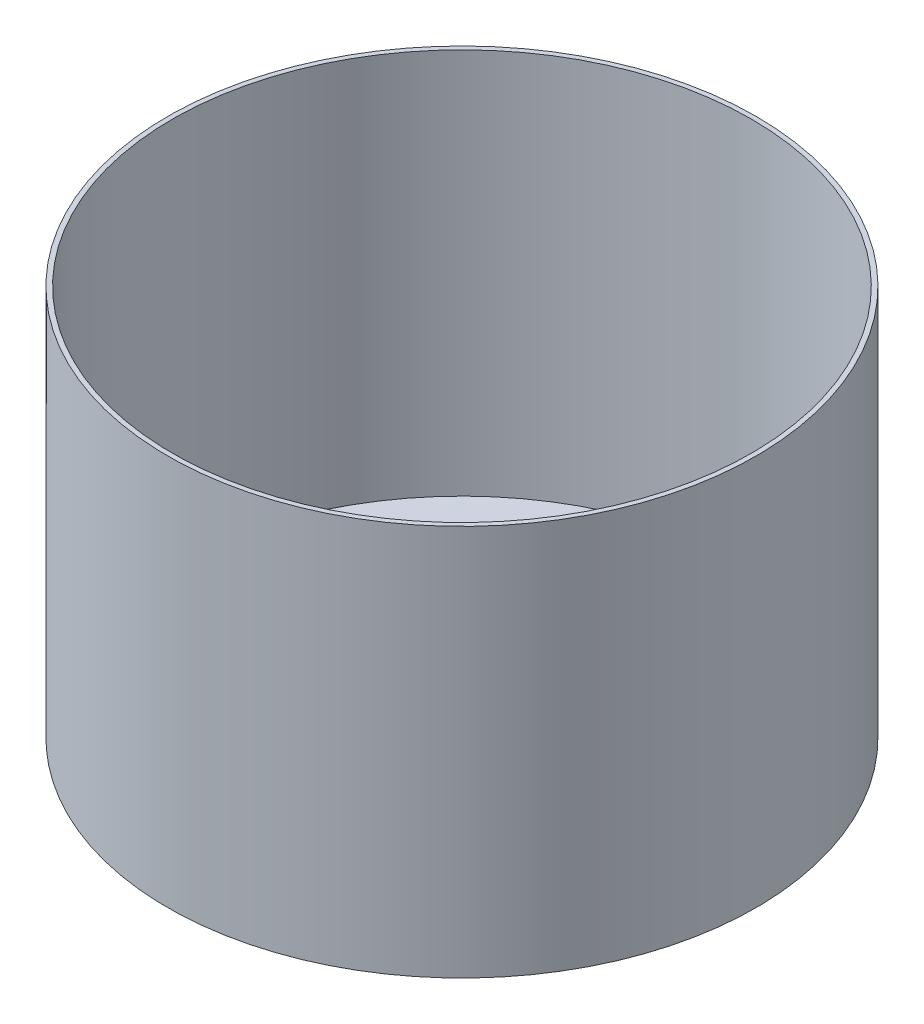
SolidWorks part; units mm, degrees
ref_plane "Front Plane" through (0, 0, 0) normal (0, 0, 1) x (1, 0, 0)
ref_plane "Top Plane" through (0, 0, 0) normal (0, 1, 0) x (1, 0, 0)
ref_plane "Right Plane" through (0, 0, 0) normal (1, 0, 0) x (0, 0, -1)
sketch "Compartment" plane through (0, 0, 0) normal (0, 0, 1) x (1, 0, 0)
  line L3 (95.504, -80) -> (0, -80)
  line L6 (93.98, 47) -> (95.504, 47)
  line L9 (93.98, 47) -> (93.98, -78.476)
  line L10 (93.98, -78.476) -> (0, -78.476)
  line L11 (0, -78.476) -> (0, -80)
  line L14 (95.504, 47) -> (95.504, -80)
  dimension "D1" = 125.476
  dimension "D2" = 1.524
  dimension "D5" = 93.98
  dimension "D6" = 1.524
  dimension "D9" = 80
ref_axis "Axis1" through (0, 0, 0) along (0, 1, 0)
revolve "Revolve1" add sketch "Compartment" angle 360 about axis through (0, 0, 0) along (0, 1, 0)
sketch "Motor Hole" plane through (0, -80, 0) normal (0, -1, 0) x (1, 0, 0)
  circle A0 centre (0, 0) radius 25.4
  circle A1 centre (0, 80.01) radius 3.048
  circle A2 centre (80.01, 0) radius 3.048
  circle A3 centre (0, -80.01) radius 3.048
  circle A4 centre (-80.01, 0) radius 3.048
  point P11 (0, 0)
  dimension "D1" = 50.8
  dimension "D2" = 6.096
  dimension "D3" = 80.01
  dimension "D4" = 80.01
  dimension "D5" = 80.01
  dimension "D6" = 80.01
extrude "Cut-Extrude2" cut sketch "Motor Hole" against normal up to next
